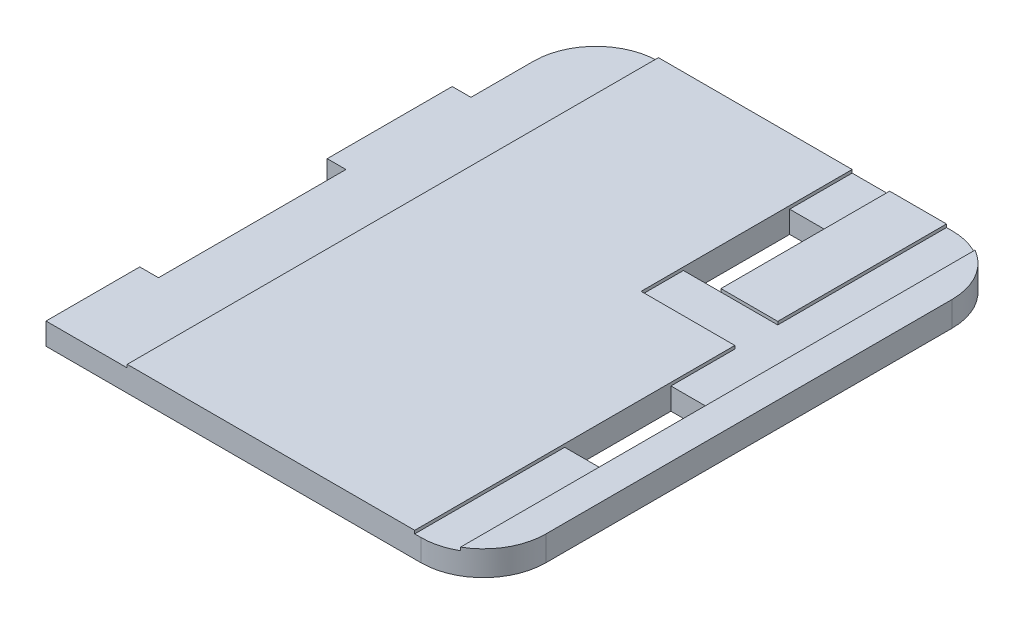
SolidWorks part; units mm, degrees
material "PBT General Purpose"
ref_plane "Front Plane" through (0, 0, 0) normal (0, 0, 1) x (1, 0, 0)
ref_plane "Top Plane" through (0, 0, 0) normal (0, 1, 0) x (1, 0, 0)
ref_plane "Right Plane" through (0, 0, 0) normal (1, 0, 0) x (0, 0, -1)
sketch "Sketch1" plane through (0, 0, 0) normal (0, 1, 0) x (1, 0, 0)
  line L0 (0, 0) -> (7, 0)
  line L5 (7, 0) -> (7, 8.5)
  line L6 (7, 8.5) -> (0.3, 8.5)
  line L7 (0.3, 8.5) -> (0.3, 6.5)
  line L8 (0.3, 6.5) -> (0, 6.5)
  line L9 (0, 6.5) -> (0, 4.5)
  line L10 (0, 4.5) -> (0.3, 4.5)
  line L11 (0.3, 4.5) -> (0.3, 1.5)
  line L12 (0.3, 1.5) -> (0, 1.5)
  line L13 (0, 1.5) -> (0, 0)
  line L15 (4.4, 7.5) -> (5, 7.5)
  line L16 (4.4, 7.5) -> (4.4, 5.8)
  line L17 (4.4, 5.8) -> (5, 5.8)
  line L18 (5, 7.5) -> (5, 5.8)
  line L19 (5.9, 2.4) -> (6.5, 2.4)
  line L20 (5.9, 2.4) -> (5.9, 4.1)
  line L21 (5.9, 4.1) -> (6.5, 4.1)
  line L22 (6.5, 2.4) -> (6.5, 4.1)
  dimension "D1" = 2
  dimension "D2" = 1.5
  dimension "D3" = 3
  dimension "D4" = 2
  dimension "D5" = 5.6
  dimension "D7" = 1.7
  dimension "D8" = 0.6
  dimension "D9" = 0.3
  dimension "D10" = 4.1
  dimension "D11" = 0.6
  dimension "D12" = 1.7
  dimension "D13" = 1
  dimension "D14" = 7
  dimension "D6" = 4.4
extrude "Boss-Extrude1" add sketch "Sketch1" along normal blind 0.4
fillet "Fillet2" radius 1 3 edges at (7, 0.2, 0) (7, 0.2, -8.5) (0.3, 0.2, -8.5)
sketch "Sketch2" plane through (0, 0.4, 0) normal (0, 1, 0) x (1, 0, 0)
  line L0 (1.3, 8.5) -> (1.3, 0)
  line L1 (0, 0) -> (6, 0) construction
  line L2 (1.3, 0) -> (-0.4801, 0)
  line L3 (-0.4801, 0) -> (-0.4801, 8.5)
  line L4 (-0.4801, 8.5) -> (1.3, 8.5)
  line L5 (4.4, 7.5) -> (4.4, 8.7942)
  line L6 (5, 7.5) -> (5, 8.7942)
  line L7 (5, 8.7942) -> (4.4, 8.7942)
  line L8 (4.4, 7.5) -> (4.4, 5.123)
  line L9 (5.9, 4.1) -> (5.9, 5.123)
  line L10 (5.9, 5.123) -> (4.4, 5.123)
  line L11 (5, 7.5) -> (5, 5.8)
  line L12 (5, 5.8) -> (5.9095, 5.8)
  line L13 (5.9, 4.1) -> (5.9, 0)
  line L14 (6.5, 4.1) -> (6.5, 0)
  line L15 (6.5, 0) -> (5.9, 0)
  line L16 (6.5, 4.1) -> (6.5, 5.123)
  line L17 (6.5, 8.5) -> (6.5, 5.123)
  line L20 (5.9095, 5.8) -> (5.9095, 8.5)
  line L21 (6, 8.5) -> (1.3, 8.5) construction
  line L22 (5.9095, 8.5) -> (6.5, 8.5)
extrude "Cut-Extrude1" cut sketch "Sketch2" against normal blind 0.05
equation "\"t\"= 0.3'thickness of the sheets"
equation "\"FlexJoint\"= 0.15'Width of flextures"
equation "\"FoldJoint\"= 0.4'Width of folding joints"
equation "\"AssembleAngle\"= 90'Angle of assembly parts"
equation "\"D9@Sketch1\"=\"t\""
